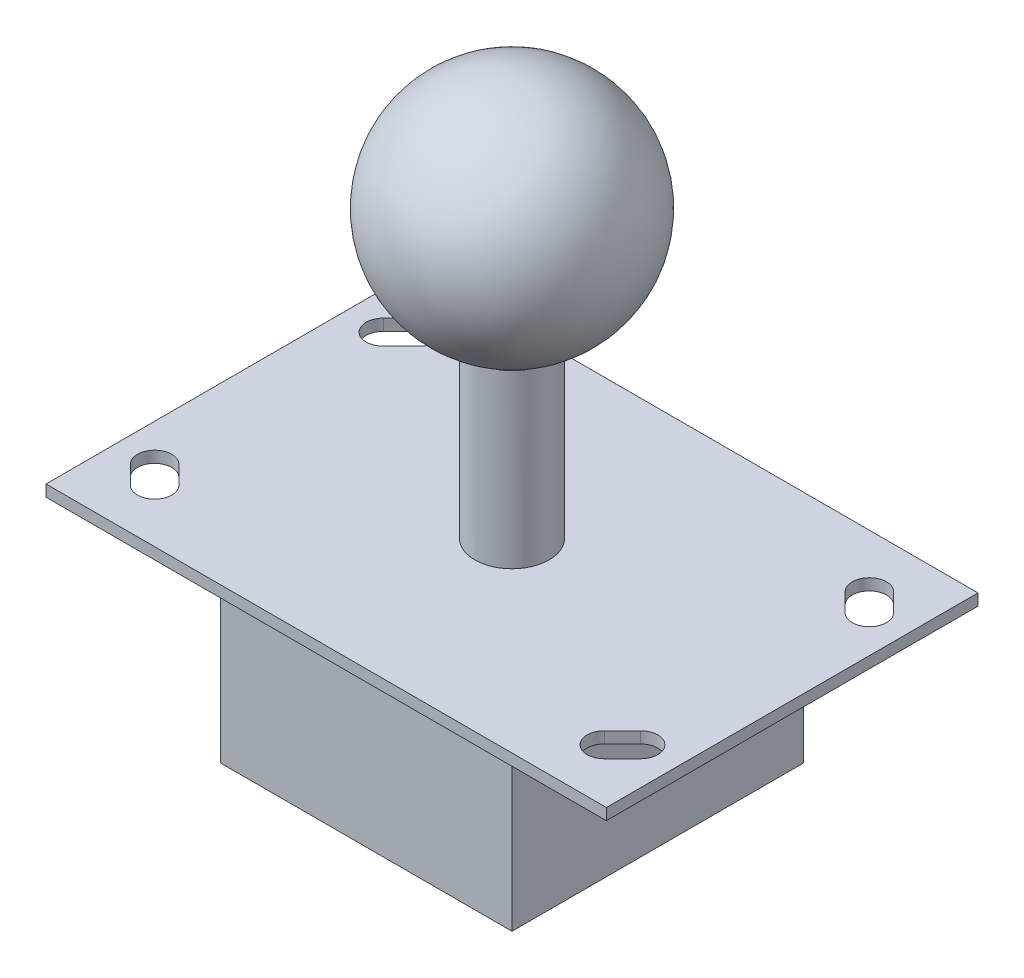
SolidWorks part; units mm, degrees
ref_plane "Front Plane" through (0, 0, 0) normal (0, 0, 1) x (1, 0, 0)
ref_plane "Top Plane" through (0, 0, 0) normal (0, 1, 0) x (1, 0, 0)
ref_plane "Right Plane" through (0, 0, 0) normal (1, 0, 0) x (0, 0, -1)
sketch "Sketch3" plane through (0, 0, 0) normal (0, 1, 0) x (1, 0, 0)
  circle A0 centre (0, 0) radius 6.5
  dimension "D1" = 13
extrude "Boss-Extrude2" add sketch "Sketch3" along normal blind 30
sketch "Sketch4" plane through (0, 0, 0) normal (0, -1, 0) x (-1, 0, 0)
  line L1 (-49, 32.5) -> (49, 32.5)
  line L2 (-49, 32.5) -> (-49, -32.5)
  line L3 (-49, -32.5) -> (49, -32.5)
  line L4 (49, 32.5) -> (49, -32.5)
  point P4 (49, 0)
  point P6 (0, 32.5)
  dimension "D1" = 98
  dimension "D2" = 65
extrude "Boss-Extrude3" add sketch "Sketch4" along normal blind 2
sketch "Sketch5" plane through (0, -2, 0) normal (0, -1, 0) x (1, 0, 0)
  line L1 (-25.5, 25.5) -> (25.5, 25.5)
  line L2 (-25.5, 25.5) -> (-25.5, -25.5)
  line L3 (-25.5, -25.5) -> (25.5, -25.5)
  line L4 (25.5, 25.5) -> (25.5, -25.5)
  point P4 (0, 25.5)
  point P6 (25.5, 0)
  dimension "D1" = 51
  dimension "D2" = 51
extrude "Boss-Extrude4" add sketch "Sketch5" along normal blind 32
sketch "Sketch7" plane through (0, 0, 0) normal (0, 1, 0) x (1, 0, 0)
  line L0 (-44.6213, 22.1213) -> (-41.4393, 25.3033)
  line L1 (-40.3787, 17.8787) -> (-37.1967, 21.0607)
  line L2 (-49, -32.5) -> (-49, 32.5) construction
  line L3 (-49, 32.5) -> (49, 32.5) construction
  line L4 (-49, 0) -> (49, 0) construction
  line L5 (49, 32.5) -> (49, -32.5) construction
  line L6 (0, 32.5) -> (0, -32.5) construction
  line L7 (49, -32.5) -> (-49, -32.5) construction
  line L8 (-44.6213, -22.1213) -> (-41.4393, -25.3033)
  line L9 (-40.3787, -17.8787) -> (-37.1967, -21.0607)
  line L10 (40.3787, -17.8787) -> (37.1967, -21.0607)
  line L11 (44.6213, -22.1213) -> (41.4393, -25.3033)
  line L12 (44.6213, 22.1213) -> (41.4393, 25.3033)
  line L13 (40.3787, 17.8787) -> (37.1967, 21.0607)
  arc A0 (-37.1967, 21.0607) -> (-41.4393, 25.3033) centre (-39.318, 23.182) ccw
  arc A1 (-44.6213, 22.1213) -> (-40.3787, 17.8787) centre (-42.5, 20) ccw
  arc A2 (-37.1967, -21.0607) -> (-41.4393, -25.3033) centre (-39.318, -23.182) cw
  arc A3 (-44.6213, -22.1213) -> (-40.3787, -17.8787) centre (-42.5, -20) cw
  arc A4 (37.1967, -21.0607) -> (41.4393, -25.3033) centre (39.318, -23.182) ccw
  arc A5 (44.6213, -22.1213) -> (40.3787, -17.8787) centre (42.5, -20) ccw
  arc A6 (37.1967, 21.0607) -> (41.4393, 25.3033) centre (39.318, 23.182) cw
  arc A7 (44.6213, 22.1213) -> (40.3787, 17.8787) centre (42.5, 20) cw
  dimension "D1" = 6
  dimension "D2" = 4.5
  dimension "D3" = 42.5
  dimension "D4" = 20
  dimension "D5" = 4.5
  dimension "D6" = 45
extrude "Cut-Extrude1" cut sketch "Sketch7" against normal through all
sketch3d "3DSketch1"
  line L0 (0, 30, 0) -> (0, 70, 0) construction
  line L1 (0, 30, 0) -> (0, 0, 0) construction
  line L2 (0, 70, 0) -> (0, 30, 0)
  arc A0 (0, 70, 0) -> (0, 30, 0) centre (0, 50, 0) ccw
  point P6 (0, 50, 20)
  dimension "D1" = 40
  dimension "D2" = 20
revolve "Revolve3" add sketch "3DSketch1" angle 360 about L0
